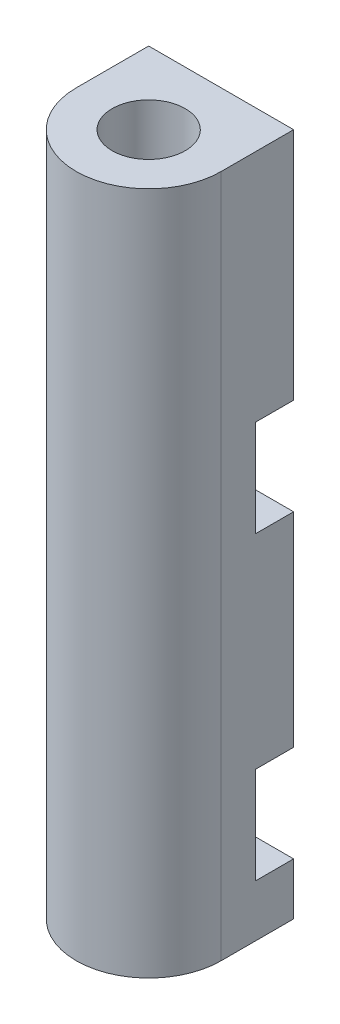
SolidWorks part; units mm, degrees
material "ABS"
ref_plane "X-Y Datum" through (0, 0, 0) normal (0, 0, 1) x (1, 0, 0)
ref_plane "X-Z Datum" through (0, 0, 0) normal (0, 1, 0) x (1, 0, 0)
ref_plane "Y-Z Datum" through (0, 0, 0) normal (1, 0, 0) x (0, 0, -1)
sketch "Sketch1" plane through (0, 0, 0) normal (0, 1, 0) x (1, 0, 0)
  line L0 (-6, 0) -> (-6, 5.43)
  line L1 (-6, 6) -> (6, 6)
  line L2 (6, 5.43) -> (6, 0)
  line L3 (0, 6) -> (0, 5.43) construction
  line L4 (-6, 5.43) -> (6, 5.43) construction
  line L5 (-6, 5.43) -> (-6, 6)
  line L6 (6, 6) -> (6, 5.43)
  arc A0 (-6, 0) -> (6, 0) centre (0, 0) ccw
  circle A1 centre (0, 0) radius 3.025
extrude "Boss-Extrude1" add sketch "Sketch1" along normal blind 56.6 contours A1 | A0 L2 L6 L1 L5 L0
ref_plane "Plane1" through (0, 28.3, 0) normal (0, 1, 0) x (1, 0, 0)
sketch "Sketch2" plane through (0, 0, -6) normal (0, 0, -1) x (-1, 0, 0)
  line L0 (0.3304, 4.308) -> (0.3304, 12.308)
  line L1 (0.3304, 4.308) -> (-7.6696, 4.308)
  line L2 (-7.6696, 4.308) -> (-7.6696, 12.308)
  line L3 (0.3304, 12.308) -> (-7.6696, 12.308)
  line L4 (0.3304, 4.308) -> (-7.6696, 12.308) construction
  line L5 (-7.6696, 4.308) -> (0.3304, 12.308) construction
  line L6 (0.3304, 29.2) -> (0.3304, 37.2)
  line L7 (0.3304, 29.2) -> (-7.6696, 29.2)
  line L8 (-7.6696, 29.2) -> (-7.6696, 37.2)
  line L9 (0.3304, 37.2) -> (-7.6696, 37.2)
  line L10 (0.3304, 29.2) -> (-7.6696, 37.2) construction
  line L11 (-7.6696, 29.2) -> (0.3304, 37.2) construction
  line L12 (-6, 0) -> (-6, 56.6) construction
  line L13 (-6, 0) -> (1.3972, 0) construction
  line L14 (1.3972, 0) -> (1.3972, 56.6) construction
  line L15 (-6, 56.6) -> (1.3972, 56.6) construction
  point P0 (-3.6696, 8.308)
  point P5 (-3.6696, 33.2)
  point P14 (-6, 56.6)
extrude "Cut-Extrude1" cut sketch "Sketch2" against normal blind 3.175
ref_plane "Plane2" through (6, 0, 0) normal (0, 0, 1) x (1, 0, 0)
